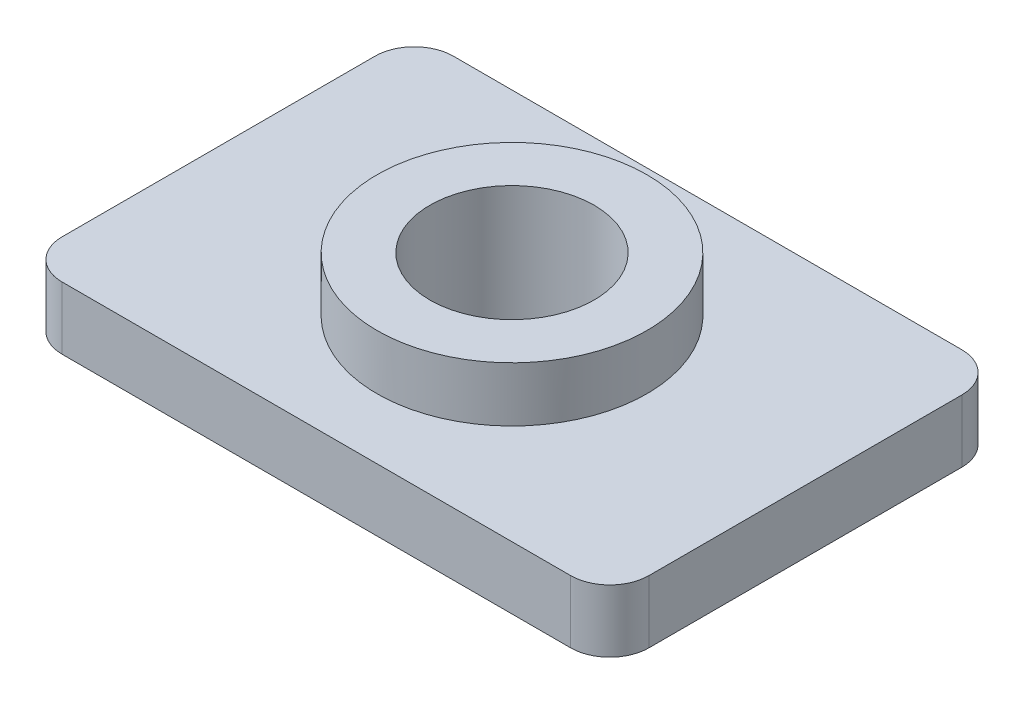
SolidWorks part; units mm, degrees
ref_plane "Alzado" through (0, 0, 0) normal (0, 0, 1) x (1, 0, 0)
ref_plane "Planta" through (0, 0, 0) normal (0, 1, 0) x (1, 0, 0)
ref_plane "Vista lateral" through (0, 0, 0) normal (1, 0, 0) x (0, 0, -1)
sketch "Croquis1" plane through (0, 0, 0) normal (0, 1, 0) x (1, 0, 0)
  line L1 (1, 0) -> (14, 0)
  line L2 (0, 1) -> (0, 9)
  line L3 (1, 10) -> (14, 10)
  line L4 (15, 1) -> (15, 9)
  arc A0 (14, 10) -> (15, 9) centre (14, 9) cw
  arc A1 (14, 0) -> (15, 1) centre (14, 1) ccw
  arc A2 (1, 0) -> (0, 1) centre (1, 1) cw
  arc A3 (0, 9) -> (1, 10) centre (1, 9) cw
  point P7 (15, 10)
  point P10 (15, 0)
  point P13 (0, 0)
  dimension "D3" = 1
  dimension "D1" = 10
  dimension "D2" = 15
extrude "Saliente-Extruir1" add sketch "Croquis1" along normal blind 1.6
sketch "Croquis2" plane through (0, 1.6, 0) normal (0, 1, 0) x (1, 0, 0)
  line L0 (0, 5) -> (15, 5) construction
  line L1 (0, 9) -> (0, 1) construction
  line L2 (15, 1) -> (15, 9) construction
  circle A0 centre (7.5, 5) radius 3.45
  dimension "D1" = 6.9
extrude "Saliente-Extruir2" add sketch "Croquis2" along normal blind 1.4
sketch "Croquis3" plane through (0, 3, 0) normal (0, 1, 0) x (1, 0, 0)
  circle A0 centre (7.5, 5) radius 2.1
  circle A1 centre (7.5, 5) radius 3.45 construction
  dimension "D1" = 4.2
extrude "Cortar-Extruir1" cut sketch "Croquis3" against normal up to next
